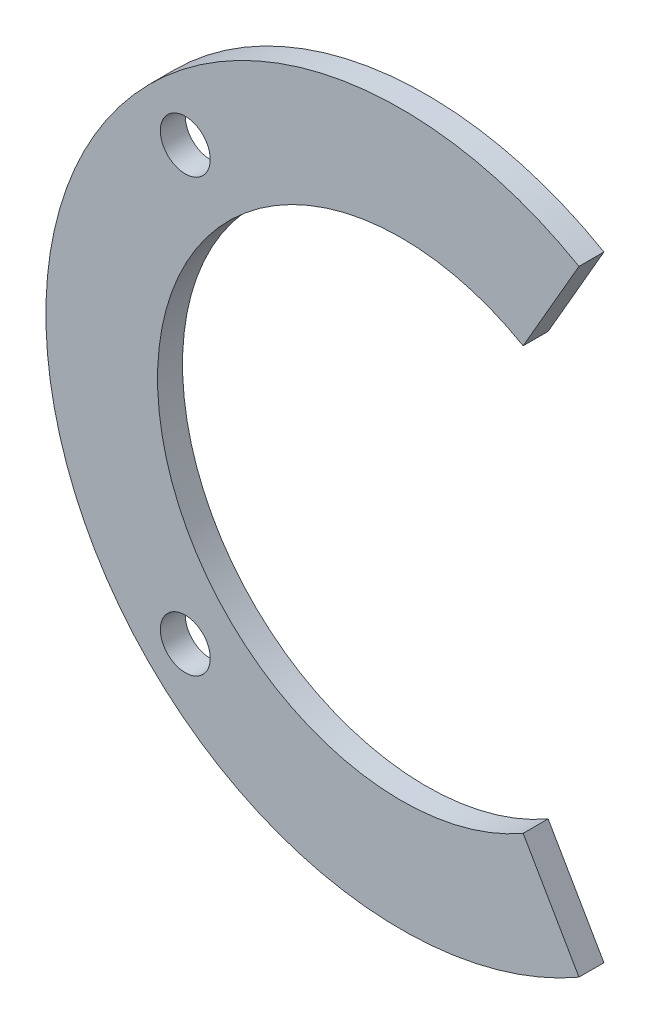
SolidWorks part; units mm, degrees
material "1060 Alloy"
ref_plane "Front Plane" through (0, 0, 0) normal (0, 0, 1) x (1, 0, 0)
ref_plane "Top Plane" through (0, 0, 0) normal (0, 1, 0) x (1, 0, 0)
ref_plane "Right Plane" through (0, 0, 0) normal (1, 0, 0) x (0, 0, -1)
sketch "Sketch2" plane through (0, 0, 0) normal (0, 0, 1) x (1, 0, 0)
  line L2 (-27.4711, 27.4711) -> (0, 0) construction
  line L3 (0, 0) -> (-27.4711, -27.4711) construction
  line L4 (22.6, 39.1443) -> (15.5, 26.8468)
  line L5 (0, 0) -> (-38.85, 0) construction
  line L6 (22.6, -39.1443) -> (15.5, -26.8468)
  arc A0 (15.5, 26.8468) -> (15.5, -26.8468) centre (0, 0) ccw
  circle A4 centre (-27.4711, -27.4711) radius 3.175
  circle A5 centre (-27.4711, 27.4711) radius 3.175
  arc A7 (22.6, 39.1443) -> (22.6, -39.1443) centre (0, 0) ccw
  circle A8 centre (0, 0) radius 38.85 construction
  dimension "D1" = 77.7
  dimension "D2" = 62
  dimension "D3" = 45.2
  dimension "D5" = 6.35
  dimension "D4" = 45
  dimension "D6" = 45
  dimension "D7" = 120
extrude "Boss-Extrude2" add sketch "Sketch2" along normal blind 3.175
